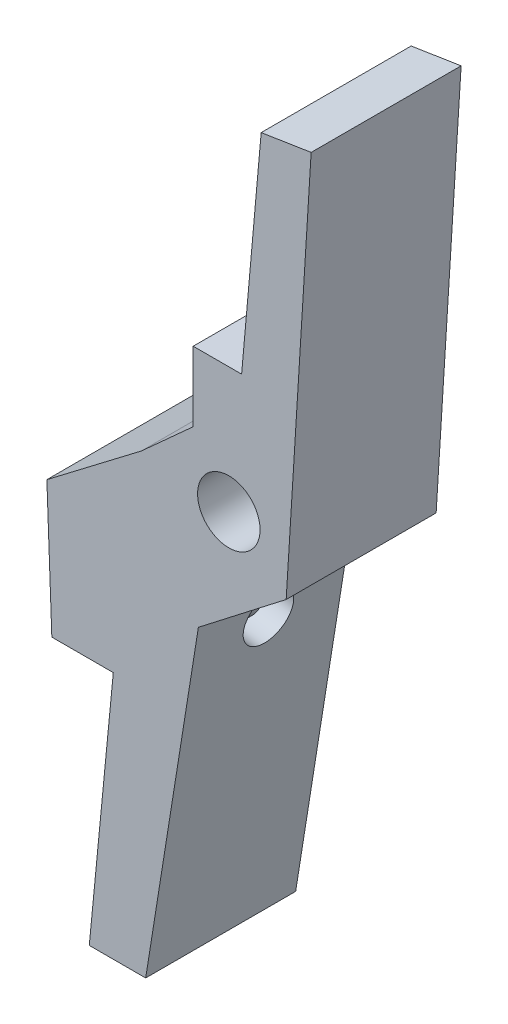
SolidWorks part; units mm, degrees
ref_plane "정면" through (0, 0, 0) normal (0, 0, 1) x (1, 0, 0)
ref_plane "윗면" through (0, 0, 0) normal (0, 1, 0) x (1, 0, 0)
ref_plane "우측면" through (0, 0, 0) normal (1, 0, 0) x (0, 0, -1)
sketch "스케치1" plane through (0, 0, 0) normal (0, 0, 1) x (1, 0, 0)
  line L0 (6.5888, 28.1968) -> (4.5888, -3.7871)
  line L1 (-2.8495, 4.4691) -> (-2.8495, 10.0473)
  line L2 (-2.8495, 10.0473) -> (1.0248, 10.0473)
  line L3 (-2.8495, 4.4691) -> (-7, 0.7109)
  line L5 (1.0248, 10.0473) -> (2.5888, 27.569)
  line L7 (4.5888, -3.7871) -> (-2.4351, -9.2249)
  line L8 (-14.1612, -15.7679) -> (-9.2429, -15.7679)
  line L9 (-9.2429, -15.7679) -> (-11.1649, -35.6343)
  line L10 (-14.5585, -5.0532) -> (-7, 0.7109)
  line L11 (-11.1649, -35.6343) -> (-6.6517, -35.6343)
  line L12 (-14.1612, -15.7679) -> (-14.5585, -5.0532)
  line L13 (6.5888, 28.1968) -> (2.5888, 27.569)
  line L14 (-6.6517, -35.6343) -> (-2.4351, -9.2249)
  circle A0 centre (0, 0) radius 2.5
  dimension "D1" = 5
  dimension "D2" = 4
  dimension "D5" = 7
extrude "보스-돌출1" add sketch "스케치1" along normal blind 12
sketch "스케치2" plane through (-0.9383, 0.1498, 0) normal (0.9875, -0.1577, 0) x (0, 0, -1)
  line L0 (-12, -9.4934) -> (0, -9.4934) construction
  circle A0 centre (-6, -11.9934) radius 2
  dimension "D1" = 4
  dimension "D2" = 2.5
extrude "컷-돌출1" cut sketch "스케치2" against normal blind 5
sketch "스케치3" plane through (-5.8757, 0.9382, 0) normal (0.9875, -0.1577, 0) x (0, 0, -1)
  circle A0 centre (-6, -11.9934) radius 1.5
  dimension "D1" = 3
extrude "보스-돌출2" add sketch "스케치3" along normal blind 4
fillet "필렛1" radius 1.5 1 edges at (-3.5802, -10.0547, 6)
